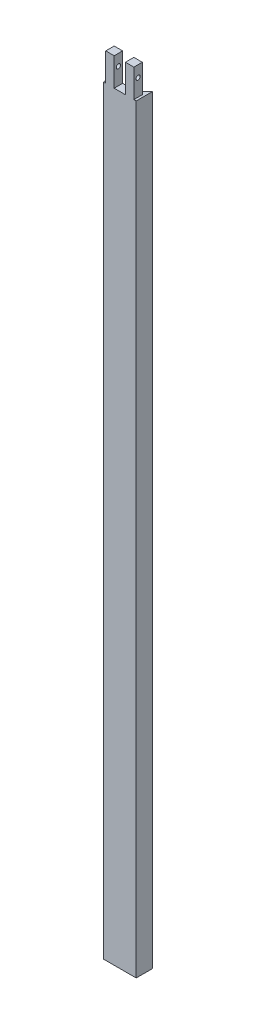
SolidWorks part; units mm, degrees
ref_plane "Front Plane" through (0, 0, 0) normal (0, 0, 1) x (1, 0, 0)
ref_plane "Top Plane" through (0, 0, 0) normal (0, 1, 0) x (1, 0, 0)
ref_plane "Right Plane" through (0, 0, 0) normal (1, 0, 0) x (0, 0, -1)
sketch "Sketch2" plane through (0, 0, 0) normal (0, 0, 1) x (1, 0, 0)
  line L1 (0, 0) -> (-6, 0)
  line L2 (0, 0) -> (0, -270)
  line L3 (0, -270) -> (-6, -270)
  line L4 (-6, 0) -> (-6, -270)
  dimension "D1" = 6
  dimension "D2" = 270
extrude "Boss-Extrude1" add sketch "Sketch2" along normal blind 3
sketch "Sketch4" plane through (0, -270, 0) normal (0, -1, 0) x (-1, 0, 0)
  line L0 (0, 0) -> (-2.8284, 2.8284)
  line L1 (-2.8284, 2.8284) -> (-2.8284, -3)
  line L2 (-2.8284, -3) -> (0, -3)
  line L3 (0, -3) -> (0, 0)
  line L4 (3, 0) -> (3, -3.7119) construction
  line L5 (6, 0) -> (0, 0) construction
  line L6 (8.8284, -3) -> (6, -3)
  line L7 (8.8284, 2.8284) -> (8.8284, -3)
  line L8 (6, 0) -> (8.8284, 2.8284)
  line L9 (6, -3) -> (6, 0)
  dimension "D1" = 135
  dimension "D2" = 4
extrude "Boss-Extrude2" add sketch "Sketch4" against normal up to vertex (270 mm away)
sketch "Sketch5" plane through (0, 0, 0) normal (0, 1, 0) x (1, 0, 0)
  line L0 (2.8284, -3) -> (-8.8284, -3) construction
  line L1 (-8, -3) -> (-5, -3)
  line L2 (-8, -3) -> (-8, 0)
  line L3 (-8, 0) -> (-5, 0)
  line L4 (-5, -3) -> (-5, 0)
  line L5 (-3, 0) -> (-3, -4.0355) construction
  line L6 (0, 0) -> (-6, 0) construction
  line L7 (2, 0) -> (-1, 0)
  line L8 (-1, -3) -> (-1, 0)
  line L9 (2, -3) -> (-1, -3)
  line L10 (2, -3) -> (2, 0)
  dimension "D1" = 3
  dimension "D2" = 2
  dimension "D3" = 0
extrude "Boss-Extrude3" add sketch "Sketch5" along normal blind 10
sketch "Sketch6" plane through (2, 0, 0) normal (1, 0, 0) x (0, 0, -1)
  line L0 (-3, 10) -> (-3, 0) construction
  line L1 (-3, 10) -> (0, 10) construction
  circle A0 centre (-1.5, 6) radius 0.75
  dimension "D1" = 1.5
  dimension "D2" = 1.5
  dimension "D3" = 4
extrude "Cut-Extrude1" cut sketch "Sketch6" against normal blind 40
